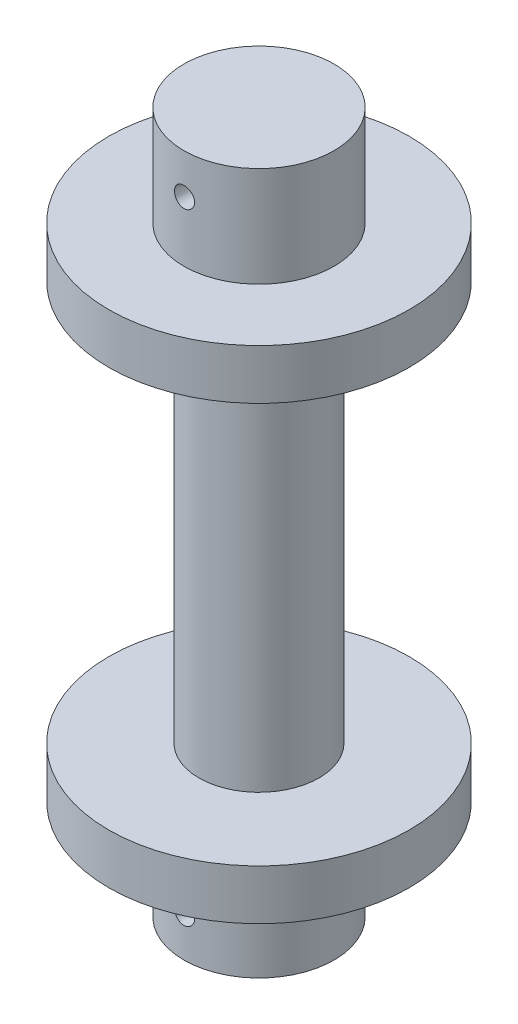
SolidWorks part; units mm, degrees
ref_plane "Front Plane" through (0, 0, 0) normal (0, 0, 1) x (1, 0, 0)
ref_plane "Top Plane" through (0, 0, 0) normal (0, 1, 0) x (1, 0, 0)
ref_plane "Right Plane" through (0, 0, 0) normal (1, 0, 0) x (0, 0, -1)
sketch "Sketch1" plane through (0, 0, 0) normal (0, 1, 0) x (1, 0, 0)
  circle A0 centre (0, 0) radius 7.5
extrude "Boss-Extrude1" add sketch "Sketch1" along normal blind 10
sketch "Sketch2" plane through (0, 10, 0) normal (0, 1, 0) x (1, 0, 0)
  circle A0 centre (0, 0) radius 15
extrude "Boss-Extrude2" add sketch "Sketch2" along normal blind 5
sketch "Sketch3" plane through (0, 15, 0) normal (0, 1, 0) x (1, 0, 0)
  circle A0 centre (0, 0) radius 6
extrude "Boss-Extrude3" add sketch "Sketch3" along normal blind 40
sketch "Sketch4" plane through (0, 55, 0) normal (0, 1, 0) x (1, 0, 0)
  circle A0 centre (0, 0) radius 15
extrude "Boss-Extrude4" add sketch "Sketch4" along normal blind 5
sketch "Sketch5" plane through (0, 60, 0) normal (0, 1, 0) x (1, 0, 0)
  circle A0 centre (0, 0) radius 7.5
extrude "Boss-Extrude5" add sketch "Sketch5" along normal blind 10
sketch "Sketch6" plane through (0, 0, 0) normal (0, 0, 1) x (1, 0, 0)
  line L0 (0, 70) -> (0, 66)
  line L2 (7.5, 70) -> (-7.5, 70) construction
  line L3 (0, 0) -> (0, 4)
  circle A0 centre (0, 4) radius 1
  circle A1 centre (0, 66) radius 1
extrude "Cut-Extrude1" cut sketch "Sketch6" against normal through all both and the other way through all contours A1 | A0
